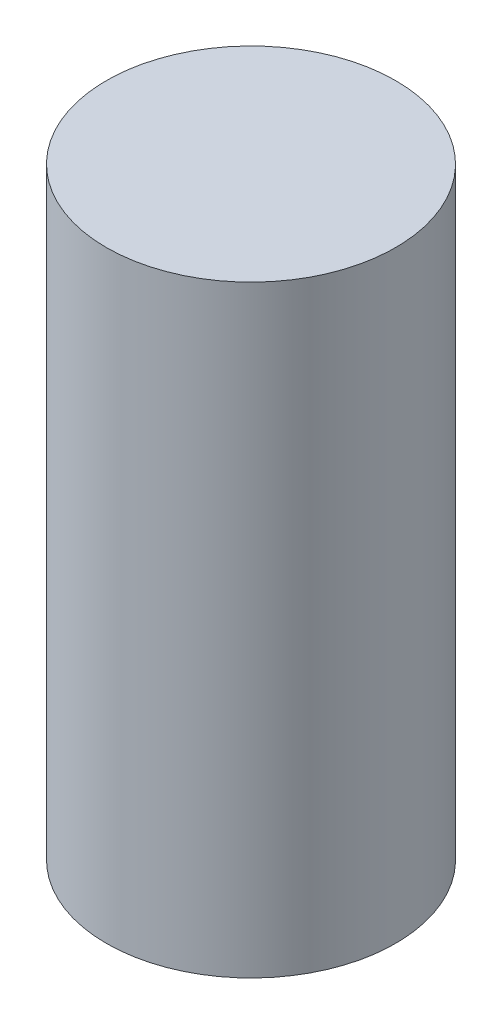
SolidWorks part; units mm, degrees
ref_plane "Front Plane" through (0, 0, 0) normal (0, 0, 1) x (1, 0, 0)
ref_plane "Top Plane" through (0, 0, 0) normal (0, 1, 0) x (1, 0, 0)
ref_plane "Right Plane" through (0, 0, 0) normal (1, 0, 0) x (0, 0, -1)
sketch "Sketch1" plane through (0, 0, 0) normal (0, 1, 0) x (1, 0, 0)
  circle A0 centre (0, 0) radius 3.048
  dimension "D1" = 6.096
extrude "Boss-Extrude1" add sketch "Sketch1" along normal mid plane 12.7
